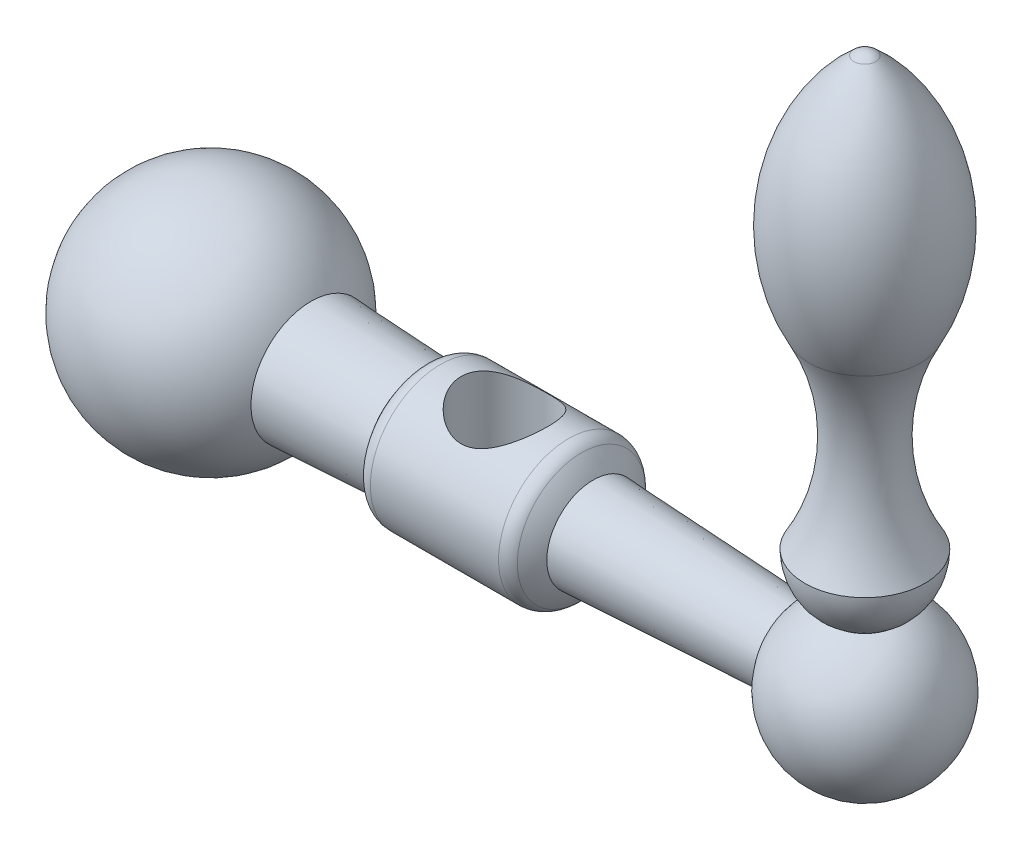
SolidWorks part; units mm, degrees
ref_plane "Ön Düzlem" through (0, 0, 0) normal (0, 0, 1) x (1, 0, 0)
ref_plane "Üst Düzlem" through (0, 0, 0) normal (0, 1, 0) x (1, 0, 0)
ref_plane "Sağ Düzlem" through (0, 0, 0) normal (1, 0, 0) x (0, 0, -1)
sketch "Çizim4" plane through (0, 0, 0) normal (0, 0, 1) x (1, 0, 0)
  line L0 (-17.5, 0) -> (17.5, 0) construction
  line L1 (17.5, 0) -> (-17.5, 0)
  arc A0 (17.5, 0) -> (-17.5, 0) centre (0, 0) ccw
  point P6 (0, 0)
revolve "Döndür2" add sketch "Çizim4" angle 360 about L0
sketch "Çizim6" plane through (0, 0, 0) normal (0, 0, 1) x (1, 0, 0)
  line L0 (0, 0) -> (44, 0) construction
  line L1 (44, 0) -> (59, 0) construction
  line L2 (34.3953, 10.5) -> (53.6047, 10.5)
  line L3 (59, 0) -> (29, 0)
  arc A0 (59, 0) -> (55.5256, 9.6) centre (44, 0) ccw
  arc A1 (32.4744, 9.6) -> (29, 0) centre (44, 0) ccw
  arc A2 (53.6047, 10.5) -> (55.5256, 9.6) centre (53.6047, 8) cw
  arc A3 (34.3953, 10.5) -> (32.4744, 9.6) centre (34.3953, 8) ccw
  point P11 (33.2879, 10.5)
  dimension "D1" = 10.5
  dimension "D4" = 2.5
  dimension "D2" = 44
  dimension "D3" = 30
revolve "Döndür3" add sketch "Çizim6" angle 360 about L3
sketch "Çizim7" plane through (0, 0, 0) normal (0, 0, 1) x (1, 0, 0)
  line L0 (0, 0) -> (98, 0) construction
  line L1 (98, 0) -> (110, 0) construction
  line L2 (86, 0) -> (110, 0)
  arc A0 (110, 0) -> (86, 0) centre (98, 0) ccw
  dimension "D1" = 98
revolve "Döndür4" add sketch "Çizim7" angle 360 about L2
sketch "Çizim8" plane through (0, 0, 0) normal (0, 0, 1) x (1, 0, 0)
  line L0 (0, 0) -> (98.6698, 0) construction
  line L1 (15.0083, 9) -> (87.3346, 5.5)
  line L2 (86, 0) -> (17.5, 0)
  circle A0 centre (98, 0) radius 12 construction
  circle A1 centre (0, 0) radius 17.5 construction
  arc A2 (87.3346, 5.5) -> (86, 0) centre (98, 0) ccw
  arc A3 (17.5, 0) -> (15.0083, 9) centre (0, 0) ccw
  dimension "D1" = 9
  dimension "D2" = 5.5
revolve "Döndür5" add sketch "Çizim8" angle 360 about L2
sketch "Çizim10" plane through (0, 0, 0) normal (0, 0, 1) x (1, 0, 0)
  line L0 (98, 0) -> (98, 83) construction
  line L1 (110, 0) -> (84.6402, 0) construction
  line L2 (93, 10.9087) -> (93, 0) construction
  line L3 (103, 10.9087) -> (103, 0) construction
  line L4 (98, 83) -> (98, 9.392)
  arc A0 (87.3346, -5.5) -> (87.3346, 5.5) centre (98, 0) ccw construction
  arc A1 (98, 83) -> (96.3774, 82.4019) centre (98, 80.5) ccw
  arc A2 (103, 10.9087) -> (93, 10.9087) centre (98, 0) ccw construction
  arc A3 (89, 18.392) -> (98, 9.392) centre (98, 18.392) ccw
  arc A4 (89, 18.392) -> (89.5997, 46.7144) centre (64, 33.089) ccw
  arc A5 (96.3774, 82.4019) -> (89.5997, 46.7144) centre (115.1995, 60.3399) ccw
  dimension "D3" = 10
  dimension "D4" = 34
  dimension "D2" = 83
revolve "Döndür6" add sketch "Çizim10" angle 360 about L4
sketch "Çizim11" plane through (0, 0, 0) normal (0, 1, 0) x (1, 0, 0)
  line L0 (34.3953, 0) -> (53.6047, 0) construction
  line L1 (34.3953, 10.5) -> (34.3953, -10.5) construction
  line L2 (53.6047, 10.5) -> (53.6047, -10.5) construction
  circle A0 centre (44, 0) radius 6.5
extrude "Kes-Ekstrüzyon1" cut sketch "Çizim11" against normal blind 19 and the other way through all
